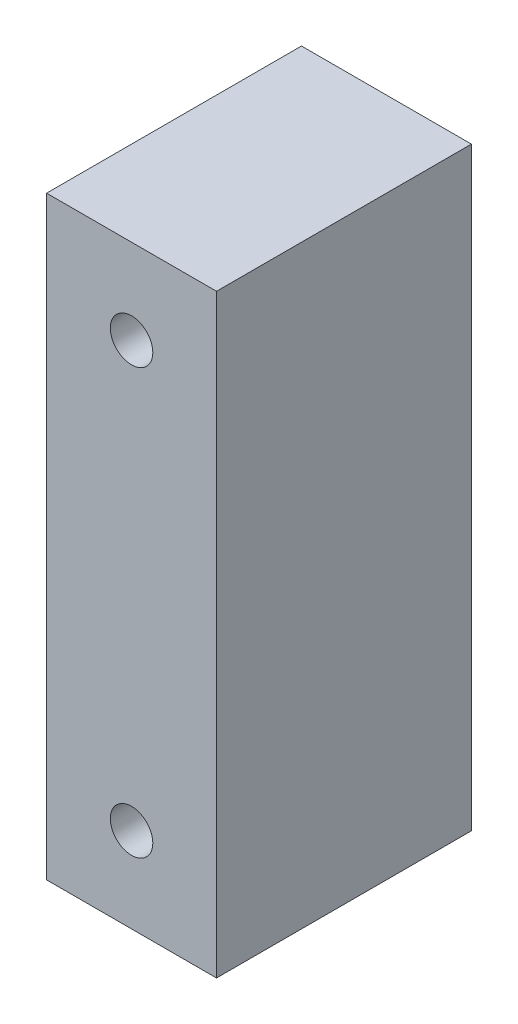
SolidWorks part; units mm, degrees
ref_plane "Front Plane" through (0, 0, 0) normal (0, 0, 1) x (1, 0, 0)
ref_plane "Top Plane" through (0, 0, 0) normal (0, 1, 0) x (1, 0, 0)
ref_plane "Right Plane" through (0, 0, 0) normal (1, 0, 0) x (0, 0, -1)
sketch "Sketch1" plane through (0, 0, 0) normal (0, 0, 1) x (1, 0, 0)
  line L1 (30, -105) -> (-30, -105)
  line L2 (30, -105) -> (30, 105)
  line L3 (30, 105) -> (-30, 105)
  line L4 (-30, -105) -> (-30, 105)
  line L5 (30, -105) -> (-30, 105) construction
  line L6 (30, 105) -> (-30, -105) construction
  point P0 (0, 0)
  dimension "D1" = 60
  dimension "D2" = 210
extrude "Boss-Extrude1" add sketch "Sketch1" along normal blind 90
sketch "Sketch2" plane through (0, 0, 90) normal (0, 0, 1) x (1, 0, 0)
  line L0 (30, 105) -> (-30, 105) construction
  line L1 (-30, -105) -> (30, -105) construction
  line L2 (-30, 105) -> (-30, -105) construction
  circle A1 centre (0, 75) radius 7.5
  circle A2 centre (0, -75) radius 7.5
  point P0 (0, 0)
  dimension "D1" = 150
  dimension "D4" = 15
  dimension "D6" = 15
  dimension "D2" = 30
  dimension "D3" = 30
  dimension "D5" = 30
extrude "Cut-Extrude1" cut sketch "Sketch2" against normal up to next
